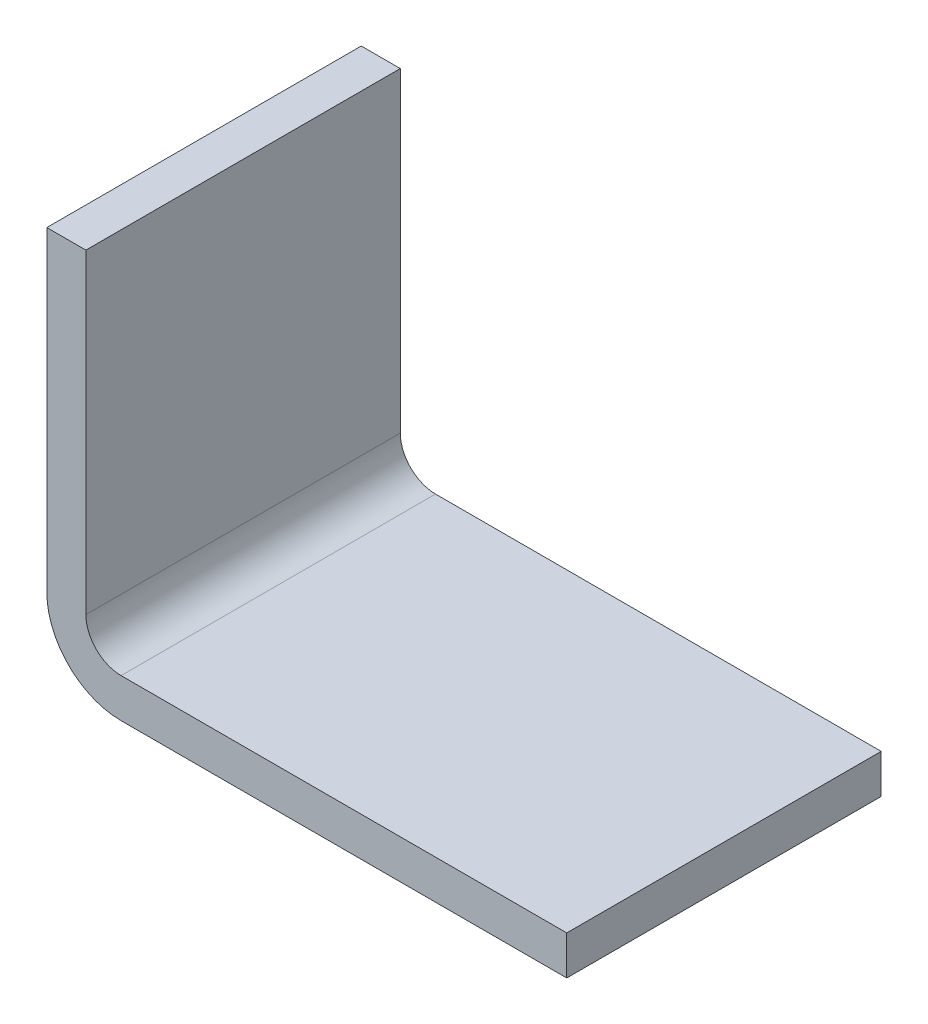
SolidWorks part; units mm, degrees
ref_plane "Alzado" through (0, 0, 0) normal (0, 0, 1) x (1, 0, 0)
ref_plane "Planta" through (0, 0, 0) normal (0, 1, 0) x (1, 0, 0)
ref_plane "Vista lateral" through (0, 0, 0) normal (1, 0, 0) x (0, 0, -1)
sketch "Croquis13" plane through (0, 0, 0) normal (0, 0, 1) x (1, 0, 0)
  line L0 (0, 0) -> (-72, 0)
  line L1 (-84, 12) -> (-84, 63)
  line L2 (0, 6.31) -> (-72, 6.31)
  line L3 (-77.69, 12) -> (-77.69, 63)
  line L4 (0, 6.31) -> (0, 0)
  line L5 (-77.69, 63) -> (-84, 63)
  arc A0 (-72, 0) -> (-84, 12) centre (-72, 12) cw
  arc A1 (-72, 6.31) -> (-77.69, 12) centre (-72, 12) cw
  point P6 (-84, 0)
  dimension "D3" = 12
  dimension "D1" = 84
  dimension "D2" = 63
  dimension "D4" = 6.31
extrude "Saliente-Extruir3" add sketch "Croquis13" along normal blind 50.8
